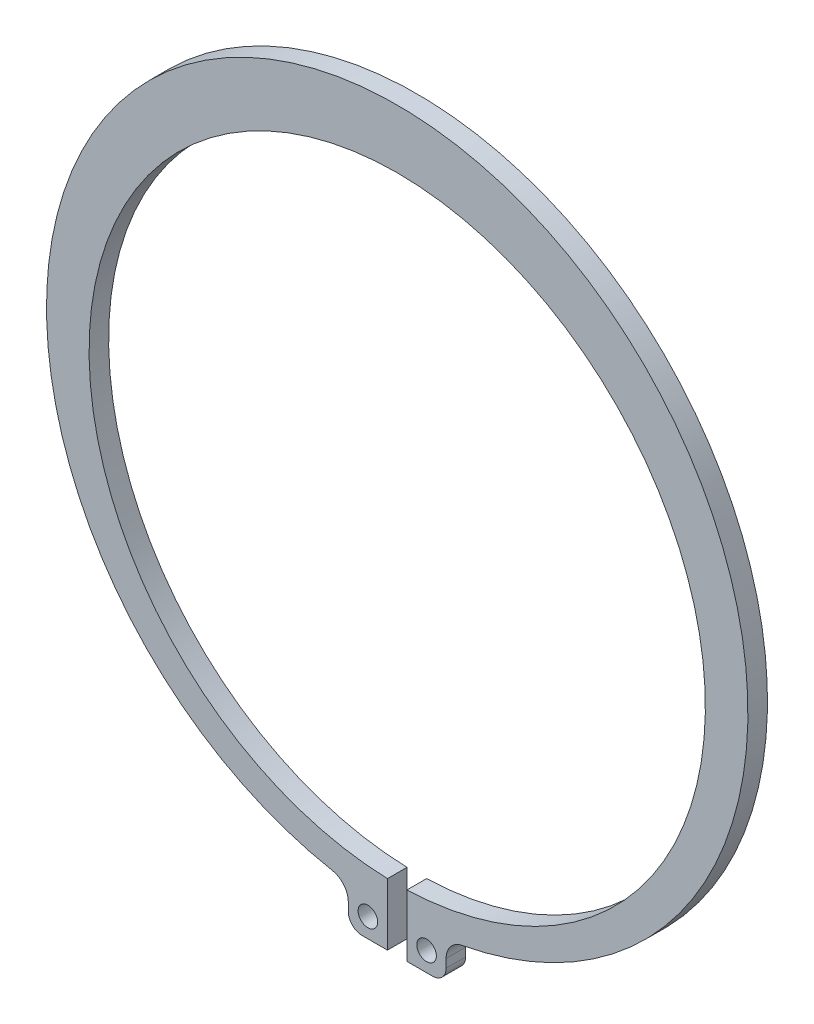
SolidWorks part; units mm, degrees
ref_plane "Front Plane" through (0, 0, 0) normal (0, 0, 1) x (1, 0, 0)
ref_plane "Top Plane" through (0, 0, 0) normal (0, 1, 0) x (1, 0, 0)
ref_plane "Right Plane" through (0, 0, 0) normal (1, 0, 0) x (0, 0, -1)
sketch "BodySke" plane through (0, 0, 0) normal (0, 0, 1) x (1, 0, 0)
  line L0 (0, 0) -> (0, 21.0564) construction
  line L1 (0, 0) -> (0, -11.0385) construction
  line L2 (-1.5, -47.2262) -> (-1.5, -56.7262)
  line L3 (-1.5, -56.7262) -> (-7.5, -56.7262)
  line L4 (-7.5, -56.7262) -> (-7.5, -50.7744)
  line L5 (7.5, -53.7503) -> (3.9811, -53.7503) construction
  line L7 (1.5, -56.7262) -> (7.5, -56.7262)
  line L8 (1.5, -47.2262) -> (1.5, -56.7262)
  line L9 (7.5, -56.7262) -> (7.5, -50.7744)
  arc A0 (1.5, -47.2262) -> (-1.5, -47.2262) centre (0, 0) ccw
  circle A2 centre (-4.5, -53.7503) radius 1.5
  circle A3 centre (4.5, -53.7503) radius 1.5
  arc A4 (7.5, -50.7744) -> (-7.5, -50.7744) centre (0, 2.475) ccw
  dimension "Groove_Diameter" = 94.5
  dimension "dia" = 3
  dimension "D3" = 53.775
  dimension "Thickness" = 3
  dimension "Groove_length" = 9.5
  dimension "Groove_Depth" = 9
  dimension "D1" = 1.5
  dimension "D2" = 1.5
extrude "BaseBody" add sketch "BodySke" along normal blind 3
fillet "Fillet1" radius 3 2 edges at (7.5, -50.7744, 1.5) (-7.5, -50.7744, 1.5)
fillet "Fillet2" radius 2.1 2 edges at (7.5, -56.7262, 1.5) (-7.5, -56.7262, 1.5)
equation "\"D1@BodySke\" = \"Thickness@BodySke\" / 2"
equation "\"D2@BodySke\" = \"Thickness@BodySke\" / 2"
equation "\"D3@BodySke\" =  ( \"Groove_Diameter@BodySke\" + 1.45 * \"Groove_Depth@BodySke\" )  / 2"
equation "\"Thickness@BaseBody\" = \"Thickness@BodySke\""
equation "\"D1@Fillet1\" = \"Thickness@BodySke\""
equation "\"D1@Fillet2\" = \"Thickness@BodySke\" * 0.7"
